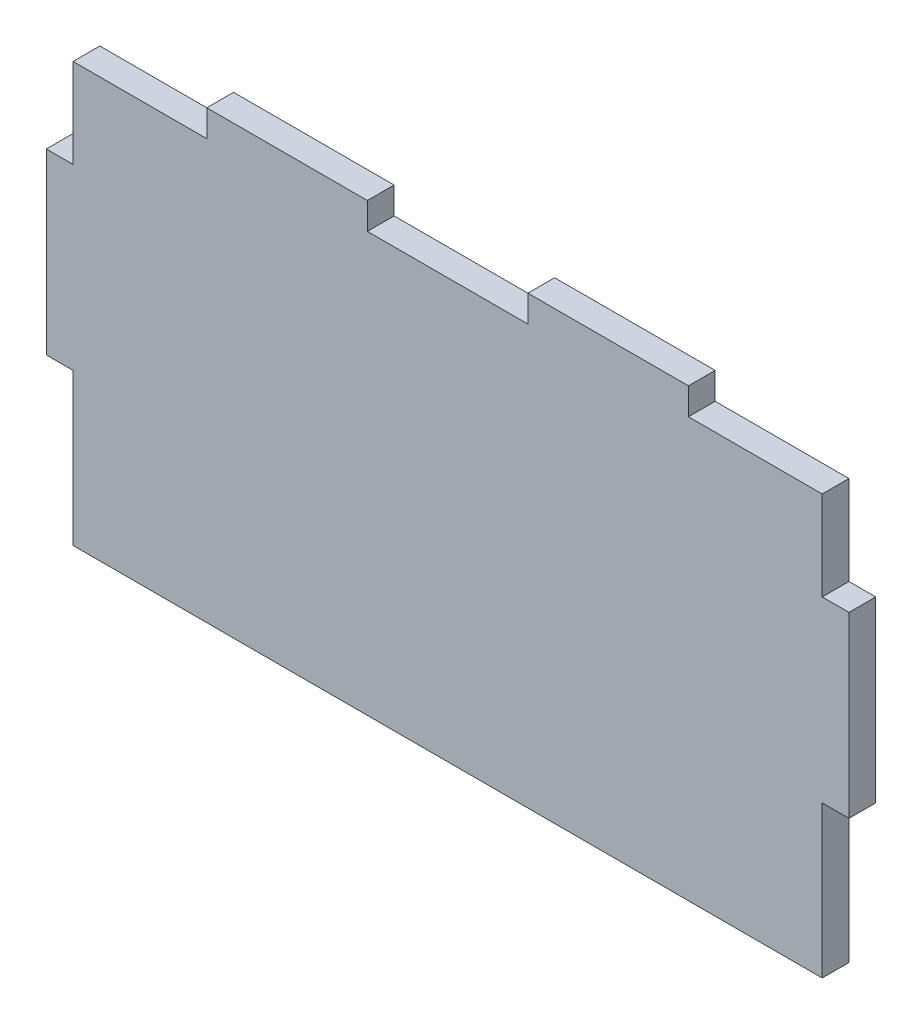
SolidWorks part; units mm, degrees
ref_plane "Front Plane" through (0, 0, 0) normal (0, 0, 1) x (1, 0, 0)
ref_plane "Top Plane" through (0, 0, 0) normal (0, 1, 0) x (1, 0, 0)
ref_plane "Right Plane" through (0, 0, 0) normal (1, 0, 0) x (0, 0, -1)
sketch "Sketch1" plane through (0, 0, 0) normal (0, 0, 1) x (1, 0, 0)
  line L1 (0, 0) -> (90, 0)
  line L2 (0, 0) -> (0, 50)
  line L3 (0, 50) -> (90, 50)
  line L4 (90, 0) -> (90, 50)
  dimension "D1" = 50
  dimension "D2" = 90
extrude "Boss-Extrude1" add sketch "Sketch1" along normal blind 3
sketch "Sketch2" plane through (0, 0, 3) normal (0, 0, 1) x (1, 0, 0)
  line L0 (90, 50) -> (0, 50) construction
  line L1 (0, 50) -> (18, 50)
  line L2 (0, 50) -> (0, 47)
  line L4 (18, 50) -> (18, 47)
  line L5 (36, 50) -> (54, 50)
  line L6 (36, 50) -> (36, 47)
  line L7 (36, 47) -> (54, 47)
  line L8 (54, 50) -> (54, 47)
  line L9 (90, 0) -> (90, 50) construction
  line L10 (90, 50) -> (72, 50)
  line L11 (90, 50) -> (90, 47)
  line L12 (18, 47) -> (3, 47)
  line L13 (72, 50) -> (72, 47)
  line L14 (90, 37) -> (87, 37)
  line L15 (90, 37) -> (90, 47)
  line L16 (72, 47) -> (87, 47)
  line L17 (87, 37) -> (87, 47)
  line L18 (0, 50) -> (0, 0) construction
  line L19 (90, 17) -> (87, 17)
  line L20 (90, 17) -> (90, 0)
  line L21 (90, 0) -> (87, 0)
  line L22 (87, 17) -> (87, 0)
  line L24 (0, 47) -> (0, 37)
  line L25 (0, 37) -> (3, 37)
  line L26 (3, 47) -> (3, 37)
  line L28 (0, 0) -> (3, 0)
  line L29 (0, 0) -> (0, 17)
  line L30 (0, 17) -> (3, 17)
  line L31 (3, 0) -> (3, 17)
  dimension "D1" = 3
  dimension "D2" = 3
  dimension "D3" = 3
  dimension "D4" = 3
  dimension "D5" = 3
  dimension "D6" = 3
  dimension "D7" = 3
  dimension "D8" = 18
  dimension "D9" = 18
  dimension "D10" = 18
  dimension "D11" = 10
  dimension "D12" = 17
  dimension "D13" = 17
  dimension "D14" = 10
  dimension "D15" = 0
  dimension "D18" = 36
extrude "Cut-Extrude1" cut sketch "Sketch2" against normal blind 3
